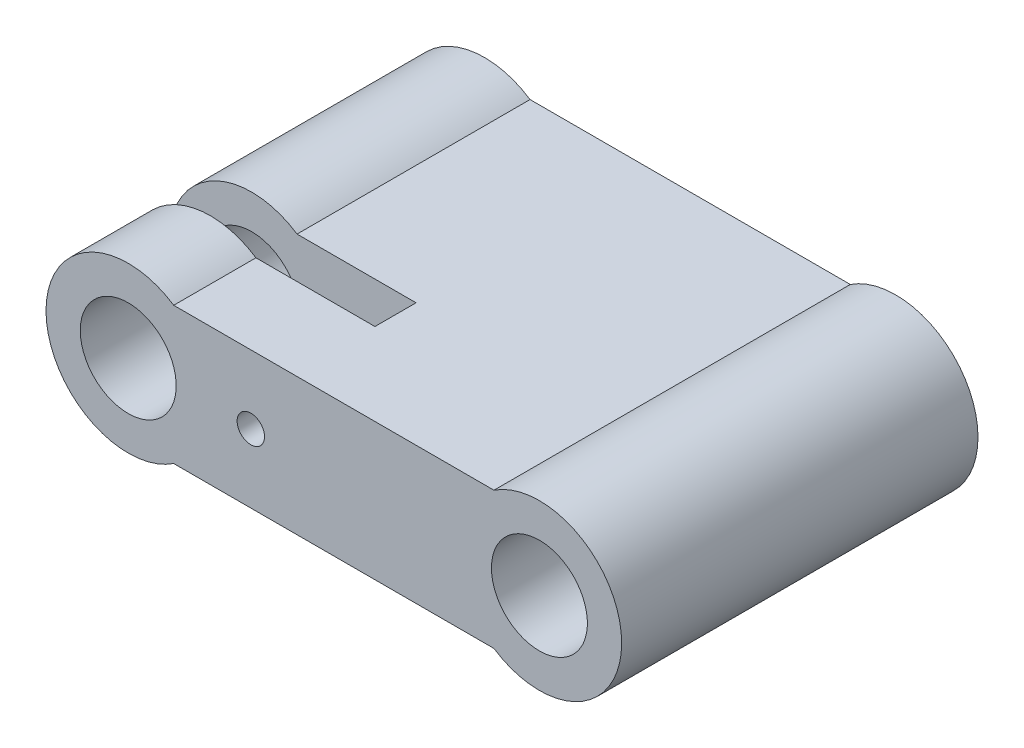
SolidWorks part; units mm, degrees
ref_plane "Front Plane" through (0, 0, 0) normal (0, 0, 1) x (1, 0, 0)
ref_plane "Top Plane" through (0, 0, 0) normal (0, 1, 0) x (1, 0, 0)
ref_plane "Right Plane" through (0, 0, 0) normal (1, 0, 0) x (0, 0, -1)
sketch "Sketch1" plane through (0, 0, 0) normal (0, 0, 1) x (1, 0, 0)
  line L4 (-71.5, -27) -> (-11.5, -27)
  line L5 (-71.5, -37) -> (-11.5, -37)
  line L6 (-71.5, -17) -> (-11.5, -17)
  circle A0 centre (-71.5, -27) radius 12
  circle A1 centre (-71.5, -27) radius 7
  circle A4 centre (-11.5, -27) radius 12
  circle A5 centre (-11.5, -27) radius 7
  circle A6 centre (-71.5, -27) radius 7 construction
  dimension "D3" = 24
  dimension "D4" = 60
  dimension "D1" = 10
  dimension "D2" = 10
extrude "Boss-Extrude1" add sketch "Sketch1" along normal offset from surface (52 mm away) 1 from offset 1
sketch "Sketch2" plane through (0, 0, 53) normal (0, 0, 1) x (1, 0, 0)
  circle A0 centre (-71.5, -27) radius 26
  arc A1 (-81.5, -3) -> (-94.5101, -14.8949) centre (-71.5, -27) ccw construction
extrude "Cut-Extrude1" cut sketch "Sketch2" along normal up to surface (6 mm away) from surface
sketch "Sketch3" plane through (0, 0, 35) normal (0, 0, 1) x (1, 0, 0)
  line L0 (-53.6115, -37) -> (-53.6115, -17) construction
  line L1 (-18.1332, -17) -> (-64.8668, -17) construction
  line L2 (-18.1332, -37) -> (-64.8668, -37) construction
  circle A0 centre (-62.5557, -11.5081) radius 2 construction
  circle A1 centre (-71.5, -27) radius 17.8885 construction
  arc A2 (-62.6756, -13.5045) -> (-62.4359, -9.5117) centre (-62.5557, -11.5081) ccw construction
  circle A3 centre (-53.6115, -27) radius 2
extrude "Cut-Extrude2" cut sketch "Sketch3" against normal through all both and the other way through all contours A3
